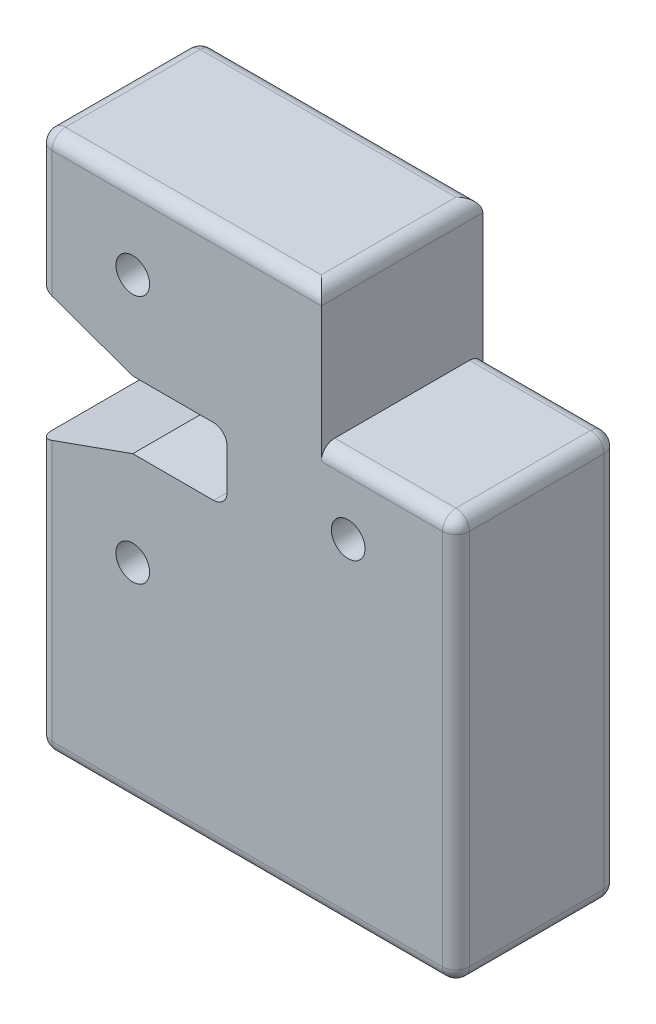
SolidWorks part; units mm, degrees
ref_plane "前视基准面" through (0, 0, 0) normal (0, 0, 1) x (1, 0, 0)
ref_plane "上视基准面" through (0, 0, 0) normal (0, 1, 0) x (1, 0, 0)
ref_plane "右视基准面" through (0, 0, 0) normal (1, 0, 0) x (0, 0, -1)
other "Configuration Table"
sketch "草图1" plane through (0, 0, 0) normal (0, 0, 1) x (1, 0, 0)
  line L0 (0, 0) -> (21, 0)
  line L1 (21, 0) -> (21, -10)
  line L2 (21, -10) -> (31, -10)
  line L3 (31, -10) -> (31, -40)
  line L4 (31, -40) -> (0, -40)
  line L5 (0, -40) -> (0, -20)
  line L6 (0, -20) -> (7, -17.5)
  line L7 (7, -17.5) -> (14, -17.5)
  line L8 (14, -17.5) -> (14, -12.5)
  line L9 (14, -12.5) -> (7, -12.5)
  line L10 (7, -12.5) -> (0, -10)
  line L11 (0, -10) -> (0, 0)
  line L12 (0, -10) -> (0, -20) construction
  line L13 (0, -15) -> (14, -15) construction
  circle A0 centre (7, -6) radius 1.25
  circle A1 centre (23, -15) radius 1.25
  circle A2 centre (7, -24.5) radius 1.25
  dimension "D11" = 2.5
  dimension "D12" = 2.5
  dimension "D13" = 2.5
  dimension "D1" = 31
  dimension "D2" = 40
  dimension "D3" = 10
  dimension "D4" = 10
  dimension "D5" = 5
  dimension "D6" = 7
  dimension "D7" = 10
  dimension "D8" = 7
  dimension "D9" = 10
  dimension "D10" = 14
  dimension "D14" = 6
  dimension "D15" = 8
  dimension "D16" = 7
  dimension "D17" = 7
  dimension "D18" = 7
extrude "凸台-拉伸1" add sketch "草图1" along normal blind 12
fillet "圆角1" radius 1 19 edges at (14, -17.5, 6) (14, -12.5, 6) (0, -30, 12) (0, -5, 12) (0, -30, 0) (0, -5, 0) (0, -40, 6) (15.5, -40, 0) (15.5, -40, 12) (31, -40, 6) (31, -25, 12) (31, -10, 6) (31, -25, 0) (26, -10, 0) (26, -10, 12) (10.5, 0, 0) (21, 0, 6) (10.5, 0, 12) (0, 0, 6)
